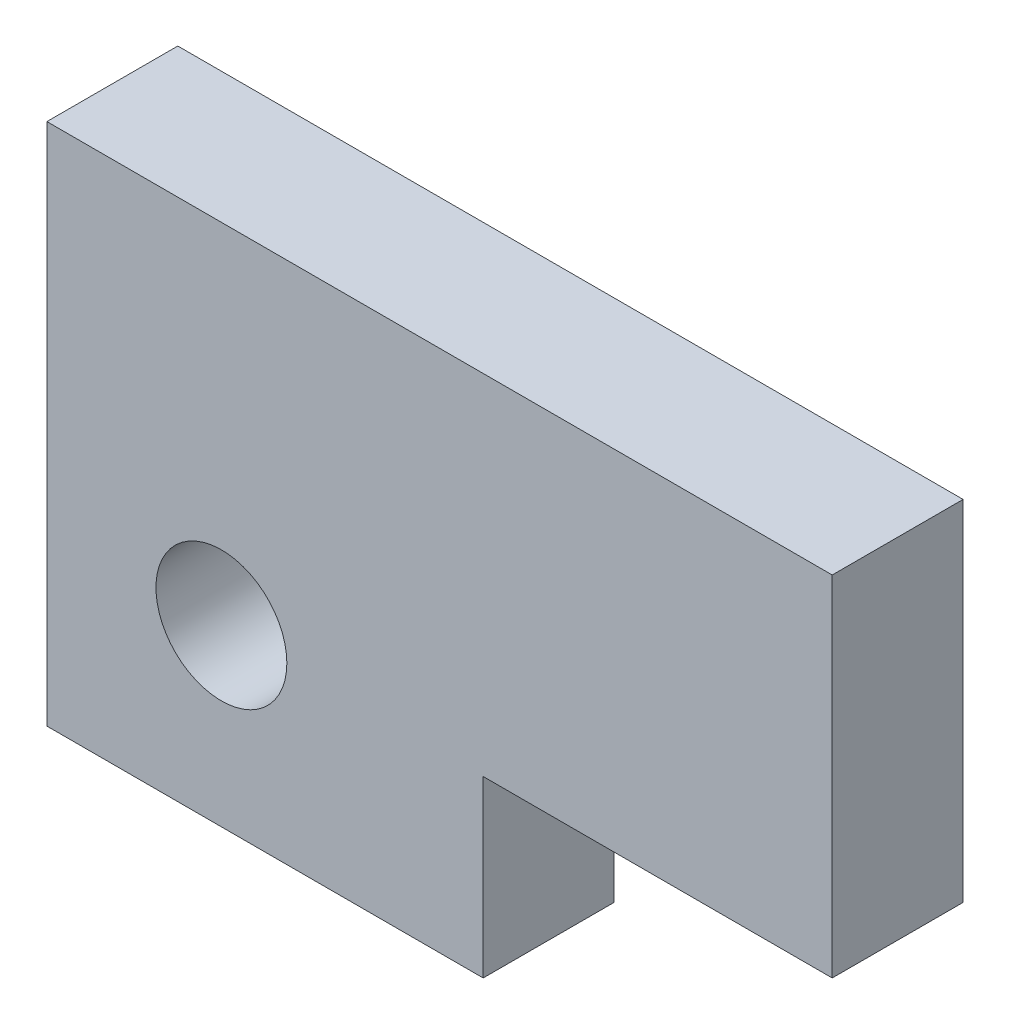
SolidWorks part; units mm, degrees
ref_plane "Спереди" through (0, 0, 0) normal (0, 0, 1) x (1, 0, 0)
ref_plane "Сверху" through (0, 0, 0) normal (0, 1, 0) x (1, 0, 0)
ref_plane "Справа" through (0, 0, 0) normal (1, 0, 0) x (0, 0, -1)
other "Configuration Table"
sketch "Эскиз1" plane through (0, 0, 0) normal (0, 0, 1) x (1, 0, 0)
  line L0 (9, 12) -> (9, 0) construction
  line L1 (0, 0) -> (10, 0)
  line L2 (0, 0) -> (0, 12)
  line L3 (0, 12) -> (18, 12)
  line L4 (18, 4) -> (18, 12)
  line L5 (0, 6) -> (18, 6) construction
  line L6 (18, 4) -> (10, 4)
  line L7 (10, 4) -> (10, 0)
  dimension "D1" = 18
  dimension "D2" = 12
  dimension "D3" = 8
  dimension "D4" = 4
extrude "Бобышка-Вытянуть1" add sketch "Эскиз1" along normal blind 3
sketch "Эскиз2" plane through (0, 0, 3) normal (0, 0, 1) x (1, 0, 0)
  line L0 (0, 0) -> (10, 0) construction
  line L7 (0, 12) -> (0, 0) construction
  circle A0 centre (4, 4) radius 1.5
  dimension "D1" = 3
  dimension "D2" = 4
  dimension "D3" = 4
extrude "Вырез-Вытянуть1" cut sketch "Эскиз2" against normal through all
